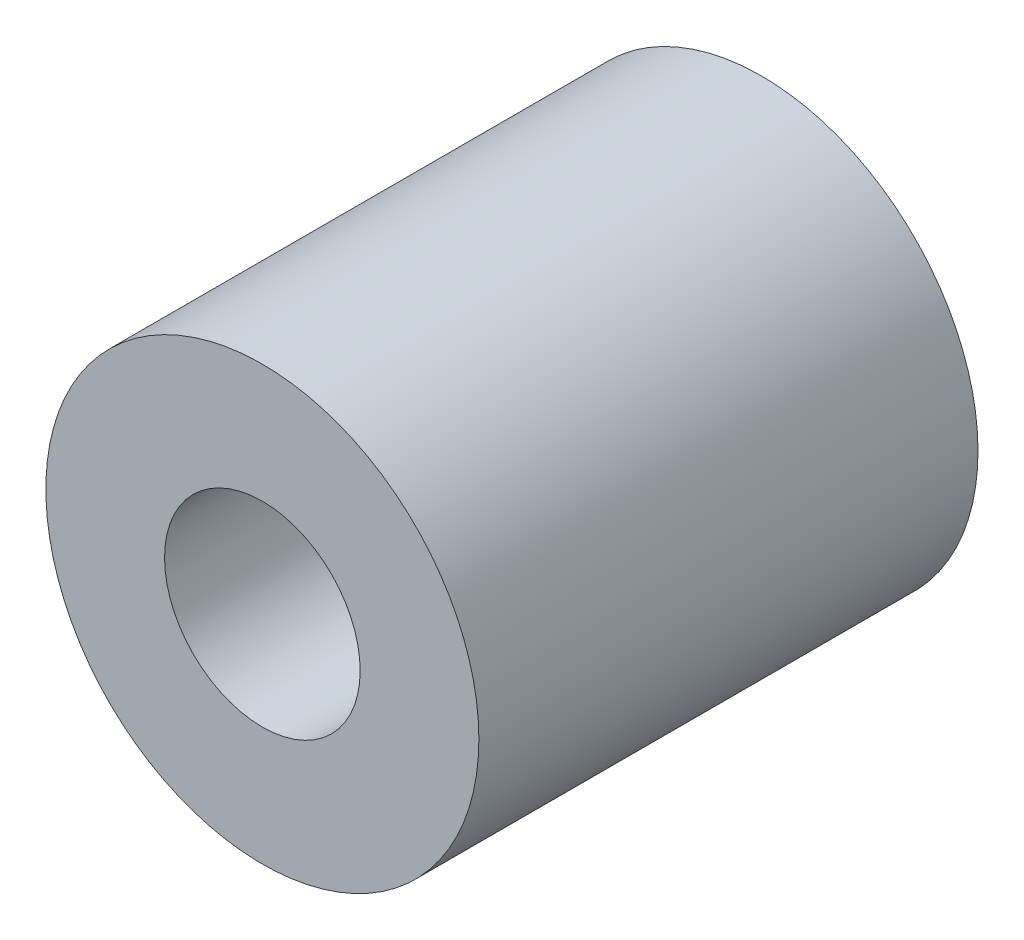
SolidWorks part; units mm, degrees
ref_plane "Front Plane" through (0, 0, 0) normal (0, 0, 1) x (1, 0, 0)
ref_plane "Top Plane" through (0, 0, 0) normal (0, 1, 0) x (1, 0, 0)
ref_plane "Right Plane" through (0, 0, 0) normal (1, 0, 0) x (0, 0, -1)
sketch "Sketch1" plane through (0, 0, 0) normal (0, 0, 1) x (1, 0, 0)
  circle A0 centre (0, 0) radius 2.4892 construction
  circle A1 centre (0, 0) radius 2.6162
  circle A2 centre (0, 0) radius 5.7912
  dimension "D1" = 4.9784
  dimension "D2" = 0.127
  dimension "D3" = 3.175
extrude "Boss-Extrude1" add sketch "Sketch1" along normal blind 13.35
